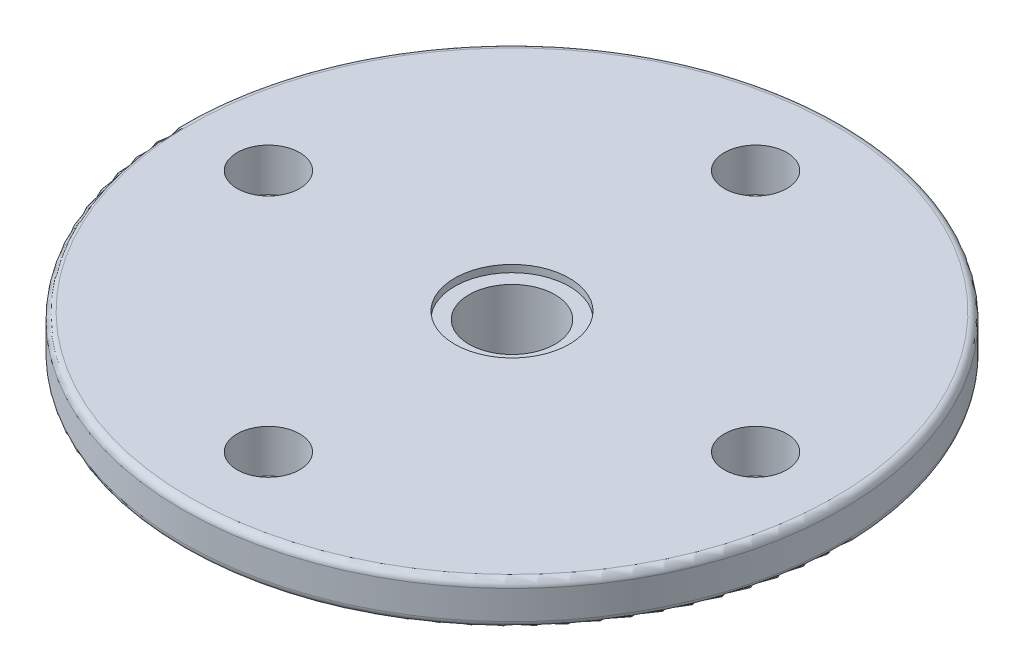
SolidWorks part; units mm, degrees
material "Plain Carbon Steel"
ref_plane "Front" through (0, 0, 0) normal (0, 0, 1) x (1, 0, 0)
ref_plane "Top" through (0, 0, 0) normal (0, 1, 0) x (1, 0, 0)
ref_plane "Right" through (0, 0, 0) normal (1, 0, 0) x (0, 0, -1)
sketch "Sketch2" plane through (0, 0, 0) normal (0, 1, 0) x (1, 0, 0)
  circle A0 centre (0, 0) radius 11.5
  circle A1 centre (0, 0) radius 1.5
  dimension "D1" = 23
  dimension "D2" = 3
extrude "Boss-Extrude1" add sketch "Sketch2" along normal blind 1.5
ref_plane "Plane1" through (0, -1, 0) normal (0, 1, 0) x (1, 0, 0)
sketch "Sketch3" plane through (0, -1, 0) normal (0, 1, 0) x (1, 0, 0)
  line L0 (0, 11.5) -> (0, -11.5) construction
  line L1 (-11.5, 0) -> (11.5, 0) construction
  line L3 (0, 11.5) -> (0, 20) construction
  line L4 (-0.625, 11.483) -> (-0.25, 20)
  line L5 (-0.25, 20) -> (0.25, 20)
  line L6 (0.625, 11.483) -> (0.25, 20)
  circle A0 centre (0, 0) radius 11.5 construction
  arc A1 (-11.5, 0) -> (11.5, 0) centre (0, 0) ccw
  arc A2 (0.625, 11.483) -> (-0.625, 11.483) centre (0, 0) ccw
  dimension "D1" = 1.25
  dimension "D2" = 0.25
  dimension "D3" = 20
extrude "Boss-Extrude2" [suppressed] add sketch "Sketch3" along normal blind 2.5 contours L6 L5 L4 A2
pattern_circular "CirPattern1" [suppressed] count 70 over 360
sketch "Sketch4" plane through (0, 1.5, 0) normal (0, 1, 0) x (1, 0, 0)
  circle A0 centre (0, 0) radius 2
  circle A1 centre (0, 0) radius 1.5
  circle A2 centre (0, 0) radius 1.5 construction
  dimension "D1" = 0.5
extrude "Cut-Extrude1" cut sketch "Sketch4" against normal blind 0.25
ref_plane "Plane2" through (0, 1.5, 0) normal (0, 1, 0) x (1, 0, 0)
sketch "Sketch5" plane through (0, 1.5, 0) normal (0, 1, 0) x (1, 0, 0)
  line L0 (-34.259, 0) -> (34.259, 0) construction
  line L1 (0, -34.259) -> (0, 34.259) construction
  circle A0 centre (0, 8.5) radius 1.09
  point P6 (0, 0)
  dimension "D1" = 8.5
  dimension "D2" = 2.18
extrude "Cut-Extrude2" cut sketch "Sketch5" against normal up to surface (1.5 mm away) up to face at (0, 0, 11.5)
pattern_circular "CirPattern2" count 4 over 360 about axis through (0, 0, 0) along (0, 1, 0) of "Cut-Extrude2"
sketch "Sketch6" plane through (0, 0, 0) normal (0, -1, 0) x (-1, 0, 0)
  circle A0 centre (0, 0) radius 1.75
  circle A1 centre (0, 0) radius 1.5
  dimension "D1" = 3.5
  dimension "D2" = 3
extrude "Boss-Extrude3" add sketch "Sketch6" along normal blind 3
sketch "Sketch7" [suppressed] plane through (0, 2.5, 0) normal (0, 1, 0) x (1, 0, 0)
  line L1 (0, 19.2244) -> (2.9845, 17.25)
  line L2 (0, 16) -> (0, 15.2756)
  line L5 (0, 18.5) -> (0, 19.2244)
  line L6 (0, 15.2756) -> (2.9845, 17.25)
  line L7 (-8.0321, 13.8378) -> (-9.2871, 16)
  arc A0 (0, 16) -> (-8.0321, 13.8378) centre (0, 0) ccw
  arc A1 (0, 18.5) -> (-9.2871, 16) centre (0, 0) ccw
  dimension "D1" = 32
  dimension "D2" = 37
  dimension "D3" = 13.7122
  dimension "D7" = 3.7756
extrude "Cut-Extrude3" [suppressed] cut sketch "Sketch7" against normal blind 1
fillet "Fillet1" radius 0.25 2 edges at (0, 0, 11.5) (0, 1.5, 11.5)
